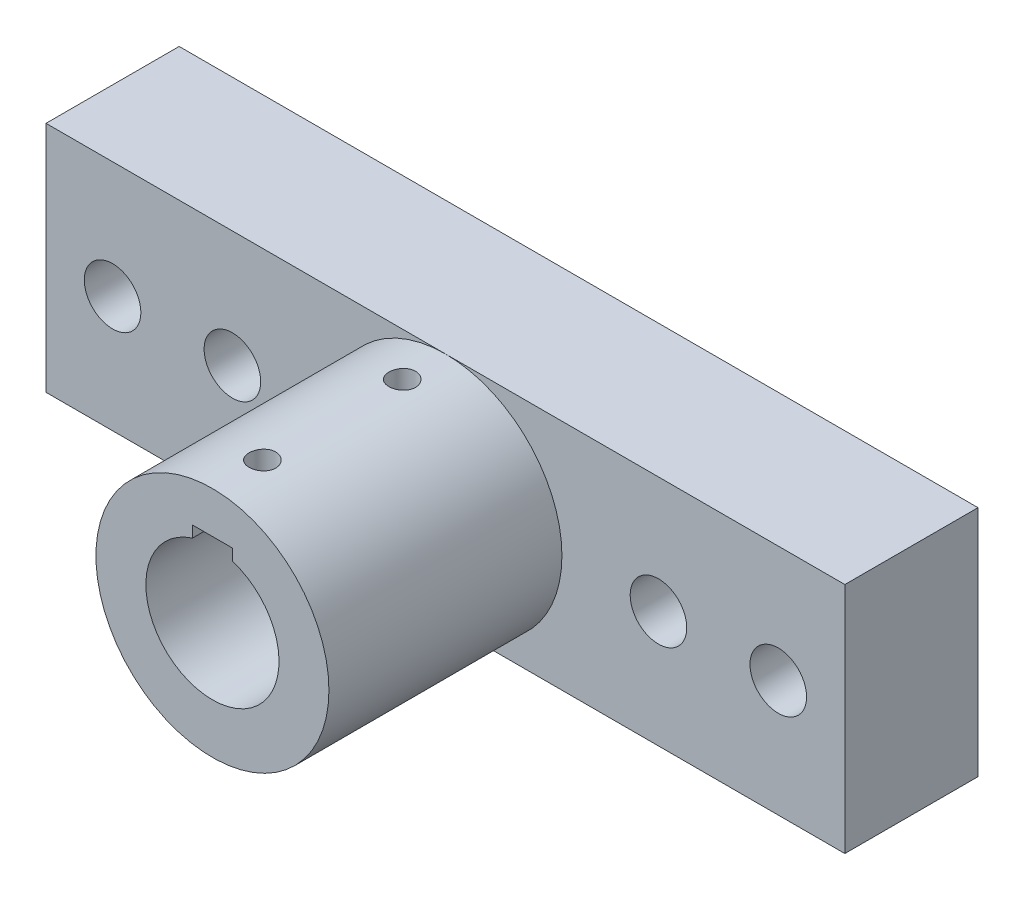
SolidWorks part; units mm, degrees
ref_plane "Front Plane" through (0, 0, 0) normal (0, 0, 1) x (1, 0, 0)
ref_plane "Top Plane" through (0, 0, 0) normal (0, 1, 0) x (1, 0, 0)
ref_plane "Right Plane" through (0, 0, 0) normal (1, 0, 0) x (0, 0, -1)
sketch "Sketch1" plane through (0, 0, 0) normal (0, 1, 0) x (1, 0, 0)
  line L0 (-60, 15) -> (60, 15)
  line L1 (-60, 15) -> (60, 15) construction
  line L2 (-60, 15) -> (-60, -40) construction
  line L3 (-60, -40) -> (60, -40) construction
  line L4 (60, 15) -> (60, -40) construction
  line L5 (60, 15) -> (60, -5)
  line L6 (60, -5) -> (17.5, -5)
  line L7 (17.5, -5) -> (17.5, -40)
  line L8 (17.5, -40) -> (-17.5, -40)
  line L9 (-17.5, -40) -> (-17.5, -5)
  line L10 (-17.5, -5) -> (-60, -5)
  line L11 (-60, -5) -> (-60, 15)
  point P1 (0, 0)
  point P13 (0, -40)
  dimension "D1" = 20
  dimension "D2" = 120
  dimension "D3" = 35
  dimension "D4" = 35
extrude "Boss-Extrude1" add sketch "Sketch1" along normal blind 35
sketch "Sketch2" plane through (0, 0, 40) normal (0, 0, 1) x (1, 0, 0)
  line L0 (0, 35) -> (0, 0) construction
  line L1 (-17.5, 35) -> (17.5, 35) construction
  line L3 (-3, 28.75) -> (3, 28.75)
  line L4 (-3, 28.75) -> (-3, 27.0394)
  line L5 (-3, 27.0394) -> (3, 27.0394)
  line L6 (3, 28.75) -> (3, 27.0394)
  line L7 (-3, 28.75) -> (3, 27.0394) construction
  line L8 (-3, 27.0394) -> (3, 28.75) construction
  circle A0 centre (0, 17.5) radius 10
  point P10 (0, 27.8947)
  dimension "D1" = 6
  dimension "D3" = 20
  dimension "D2" = 11.25
extrude "Cut-Extrude1" cut sketch "Sketch2" against normal through all contours A0 L6 L3 L4 | L5 A0 | L5 A0
sketch "Sketch3" plane through (0, 0, 5) normal (0, 0, 1) x (1, 0, 0)
  line L0 (0, 35) -> (0, 0) construction
  line L1 (-17.5, 35) -> (17.5, 35) construction
  line L2 (-60, 17.5) -> (-17.5, 17.5) construction
  line L3 (-60, 35) -> (-60, 0) construction
  line L4 (-17.5, 35) -> (-17.5, 0) construction
  circle A0 centre (-50, 17.5) radius 4.25
  circle A1 centre (-32, 17.5) radius 4.25
  circle A2 centre (32, 17.5) radius 4.25
  circle A3 centre (50, 17.5) radius 4.25
  dimension "D1" = 8.5
  dimension "D2" = 8.5
  dimension "D3" = 10
  dimension "D4" = 18
extrude "Cut-Extrude2" cut sketch "Sketch3" against normal through all
sketch "Sketch4" plane through (0, 0, 40) normal (0, 0, 1) x (1, 0, 0)
  line L1 (-17.5, 35) -> (17.5, 35)
  line L2 (-17.5, 35) -> (-17.5, 0)
  line L3 (-17.5, 0) -> (17.5, 0)
  line L4 (17.5, 35) -> (17.5, 0)
  circle A0 centre (0, 17.5) radius 17.5
  line M5 (-17.5, 0) -> (17.5, 0)
  line M6 (17.5, 0) -> (17.5, 35)
  line M7 (17.5, 35) -> (-17.5, 35)
  line M8 (-17.5, 35) -> (-17.5, 0)
extrude "Cut-Extrude6" cut sketch "Sketch4" against normal up to surface (35 mm away) contours A0 L1 M8 | A0 L4 M7 | A0 L3 M6 | A0 L2 M5 up to face at (-45.75, 17.5, 5)
sketch "Sketch5" plane through (0, 35, 0) normal (0, 1, 0) x (1, 0, 0)
  line L0 (0, -40) -> (0, -5) construction
  line L1 (-17.5, -40) -> (17.5, -40) construction
  circle A0 centre (0, -32.5) radius 2
  circle A1 centre (0, -11.5) radius 2
  dimension "D1" = 4
  dimension "D2" = 4
  dimension "D3" = 21
  dimension "D4" = 7.5
extrude "Cut-Extrude7" cut sketch "Sketch5" against normal up to next
